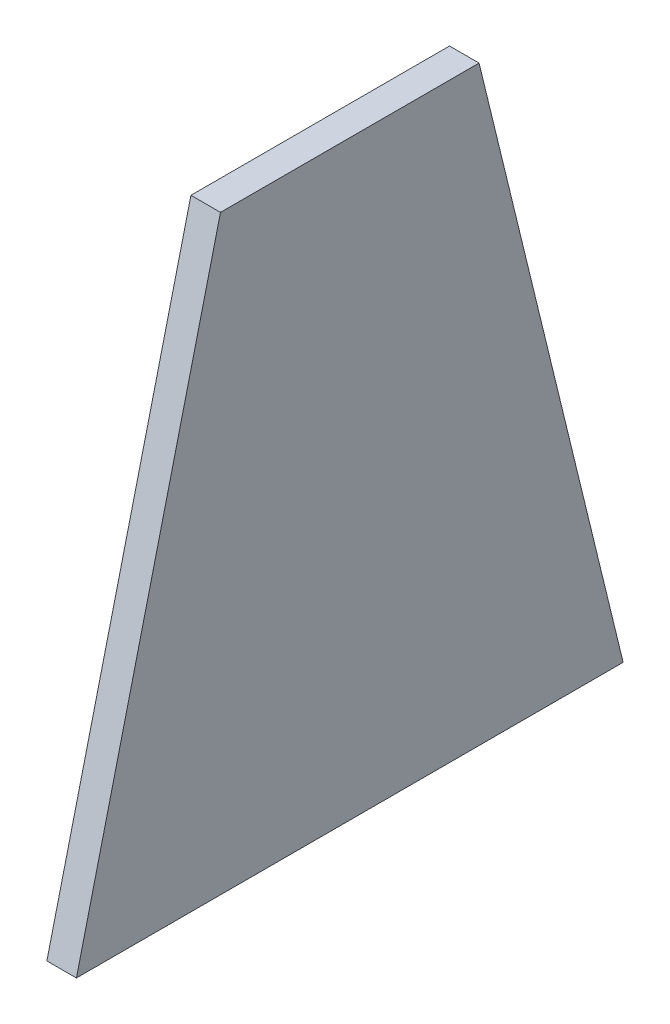
SolidWorks part; units mm, degrees
ref_plane "Front Plane" through (0, 0, 0) normal (0, 0, 1) x (1, 0, 0)
ref_plane "Top Plane" through (0, 0, 0) normal (0, 1, 0) x (1, 0, 0)
ref_plane "Right Plane" through (0, 0, 0) normal (1, 0, 0) x (0, 0, -1)
sketch "Sketch2" plane through (0, 0, 0) normal (1, 0, 0) x (0, 0, -1)
  line L0 (0, 0) -> (0, 0.2515)
  line L1 (17.5, 80) -> (-17.5, 80)
  line L2 (-17.5, 80) -> (-37, 0)
  line L3 (-37, 0) -> (37, 0)
  line L4 (17.5, 80) -> (37, 0)
  dimension "D1" = 37
extrude "Boss-Extrude1" add sketch "Sketch2" along normal blind 4 contours L1 L2 L3 L4
